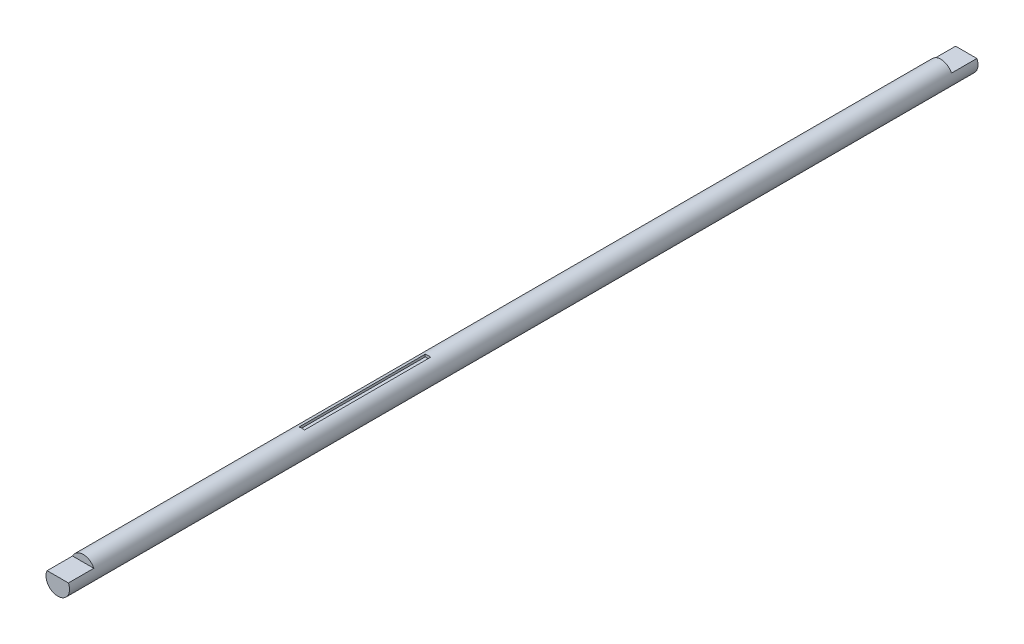
SolidWorks part; units mm, degrees
ref_plane "Alzado" through (0, 0, 0) normal (0, 0, 1) x (1, 0, 0)
ref_plane "Planta" through (0, 0, 0) normal (0, 1, 0) x (1, 0, 0)
ref_plane "Vista lateral" through (0, 0, 0) normal (1, 0, 0) x (0, 0, -1)
sketch "Sketch1" plane through (0, 0, 0) normal (0, 0, 1) x (1, 0, 0)
  circle A0 centre (0, 0) radius 7
  dimension "D1" = 14
extrude "Boss-Extrude1" add sketch "Sketch1" along normal mid plane 540
sketch "Sketch2" plane through (0, 0, 270) normal (0, 0, 1) x (1, 0, 0)
  line L0 (-6.3246, 3) -> (6.3246, 3)
  circle A0 centre (0, 0) radius 7 construction
  arc A1 (-6.3246, 3) -> (6.3246, 3) centre (0, 0) cw
  circle A2 centre (0, 0) radius 7 construction
  dimension "D1" = 4
extrude "Cut-Extrude1" cut sketch "Sketch2" against normal blind 15.1
sketch "Sketch3" plane through (0, 0, 270) normal (0, 0, 1) x (1, 0, 0)
  line L0 (0, 0) -> (0, 7) construction
  line L1 (1.5875, 5.4125) -> (-1.5875, 5.4125)
  line L2 (1.5875, 5.4125) -> (1.5875, 8.5875)
  line L3 (1.5875, 8.5875) -> (-1.5875, 8.5875)
  line L4 (-1.5875, 5.4125) -> (-1.5875, 8.5875)
  line L5 (1.5875, 5.4125) -> (-1.5875, 8.5875) construction
  line L6 (1.5875, 8.5875) -> (-1.5875, 5.4125) construction
  arc A0 (6.3246, 3) -> (-6.3246, 3) centre (0, 0) ccw construction
  point P0 (0, 7)
  dimension "D2" = 1.5875
  dimension "D1" = 3.175
extrude "Cut-Extrude2" cut sketch "Sketch3" against normal blind 75 from offset 145 offset against normal yes
mirror "Mirror1" about plane through (0, 0, 0) normal (0, 0, 1) of "Cut-Extrude1"
sketch "Sketch4" plane through (0, 0, 270) normal (0, 0, 1) x (1, 0, 0)
  circle A0 centre (0, 0) radius 2.5
  dimension "D1" = 5
sketch "Sketch5" plane through (0, 3, 0) normal (0, 1, 0) x (1, 0, 0)
  line L1 (-6.3246, -270) -> (6.3246, -270) construction
